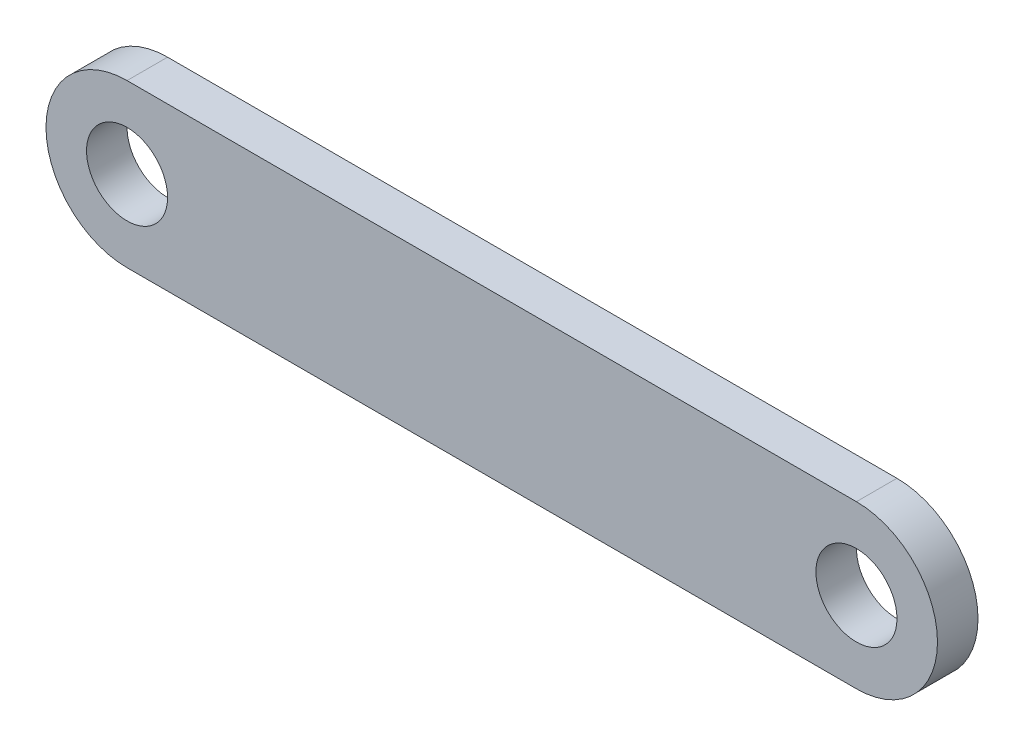
SolidWorks part; units mm, degrees
ref_plane "Front Plane" through (0, 0, 0) normal (0, 0, 1) x (1, 0, 0)
ref_plane "Top Plane" through (0, 0, 0) normal (0, 1, 0) x (1, 0, 0)
ref_plane "Right Plane" through (0, 0, 0) normal (1, 0, 0) x (0, 0, -1)
sketch "Sketch1" plane through (0, 0, 0) normal (0, 0, 1) x (1, 0, 0)
  line L0 (-22.5, 0) -> (22.5, 0) construction
  line L1 (-22.5, 0) -> (22.5, 0) construction
  line L2 (-22.5, 5) -> (22.5, 5)
  line L3 (-22.5, -5) -> (22.5, -5)
  arc A0 (-22.5, 5) -> (-22.5, -5) centre (-22.5, 0) ccw
  arc A1 (22.5, -5) -> (22.5, 5) centre (22.5, 0) ccw
  circle A2 centre (-22.5, 0) radius 2.5
  circle A3 centre (22.5, 0) radius 2.5
  point P3 (0, 0)
  point P4 (0, 0)
  dimension "D1" = 45
extrude "Boss-Extrude1" add sketch "Sketch1" along normal blind 2.5
